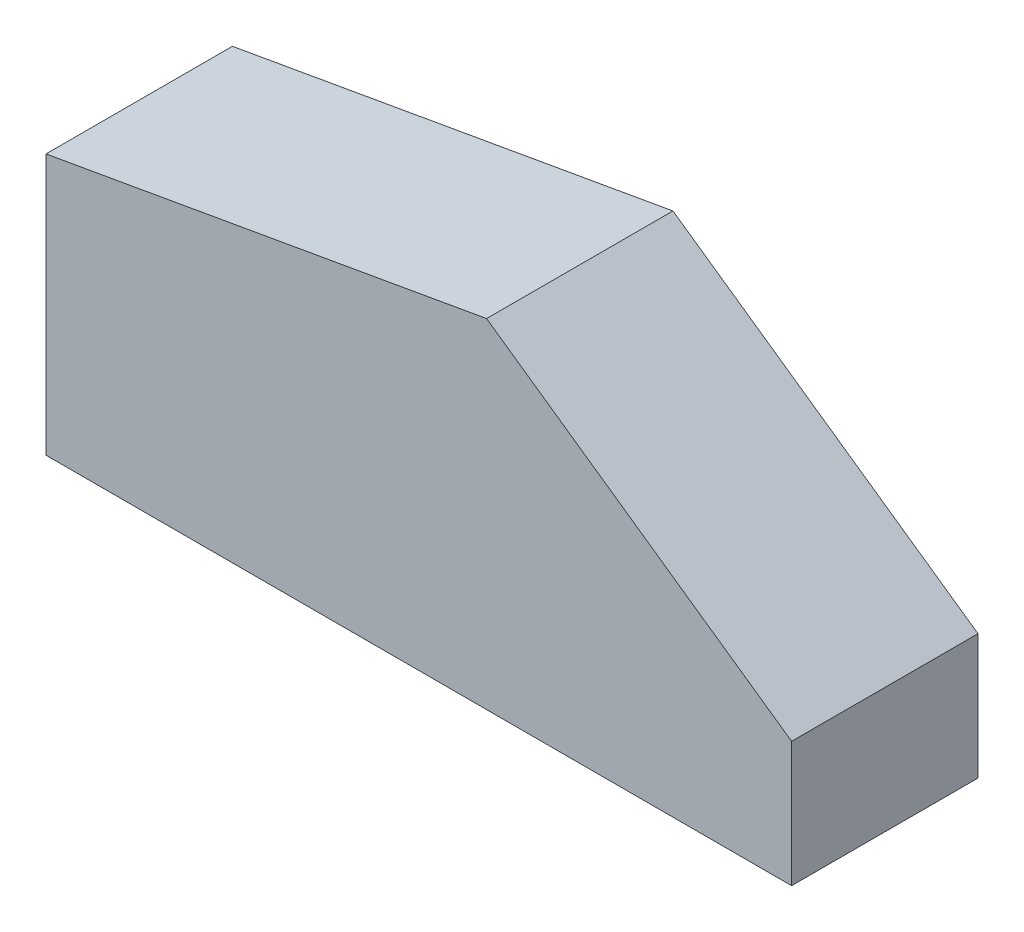
SolidWorks part; units mm, degrees
ref_plane "Front Plane" through (0, 0, 0) normal (0, 0, 1) x (1, 0, 0)
ref_plane "Top Plane" through (0, 0, 0) normal (0, 1, 0) x (1, 0, 0)
ref_plane "Right Plane" through (0, 0, 0) normal (1, 0, 0) x (0, 0, -1)
sketch "Sketch2" plane through (0, 0, 0) normal (0, 0, 1) x (1, 0, 0)
  line L0 (0, 0) -> (100, 0)
  line L1 (100, 0) -> (100, 16.7723)
  line L2 (100, 16.7723) -> (59.0885, 45.4189)
  line L3 (59.0885, 45.4189) -> (0, 35)
  line L4 (0, 35) -> (0, 0)
  dimension "D1" = 35
  dimension "D2" = 100
  dimension "D3" = 60
  dimension "D4" = 100
  dimension "D5" = 135
extrude "Boss-Extrude1" add sketch "Sketch2" along normal blind 25 contours L3 L4 L0 L1 L2
